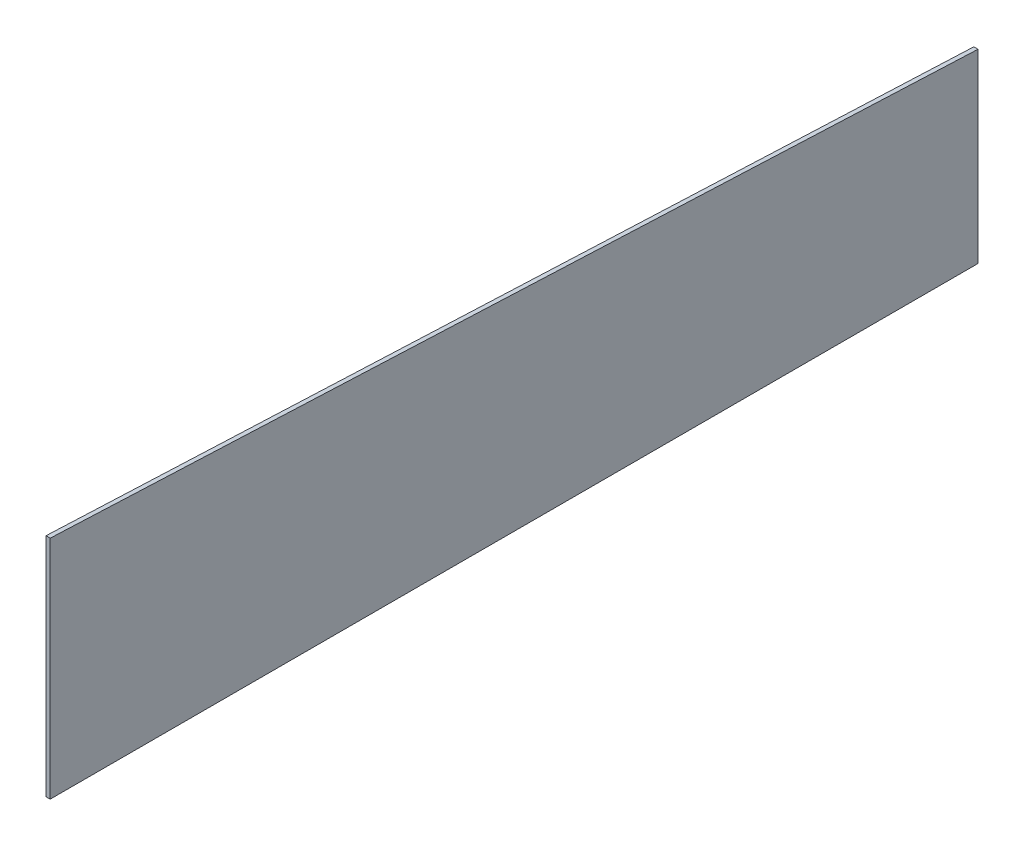
SolidWorks part; units mm, degrees
ref_plane "Front Plane" through (0, 0, 0) normal (0, 0, 1) x (1, 0, 0)
ref_plane "Top Plane" through (0, 0, 0) normal (0, 1, 0) x (1, 0, 0)
ref_plane "Right Plane" through (0, 0, 0) normal (1, 0, 0) x (0, 0, -1)
sketch "Sketch1" plane through (0, 0, 0) normal (1, 0, 0) x (0, 0, -1)
  line L1 (0, 0) -> (698.5, 0)
  line L2 (0, 0) -> (0, 139.7)
  line L4 (698.5, 0) -> (698.5, 139.7)
  line L5 (0, 139.7) -> (698.5, 139.7) construction
  line L6 (0, 170.1972) -> (698.5, 139.7)
  line L7 (0, 170.1972) -> (0, 139.7)
  line L8 (0, 139.7) -> (0, 170.1972) construction
  line L9 (0, 170.1972) -> (698.5, 170.1972) construction
  line L10 (698.5, 170.1972) -> (698.5, 139.7) construction
  dimension "D1" = 139.7
  dimension "D2" = 698.5
  dimension "D3" = 2.5
extrude "Boss-Extrude1" add sketch "Sketch1" along normal blind 3.175
